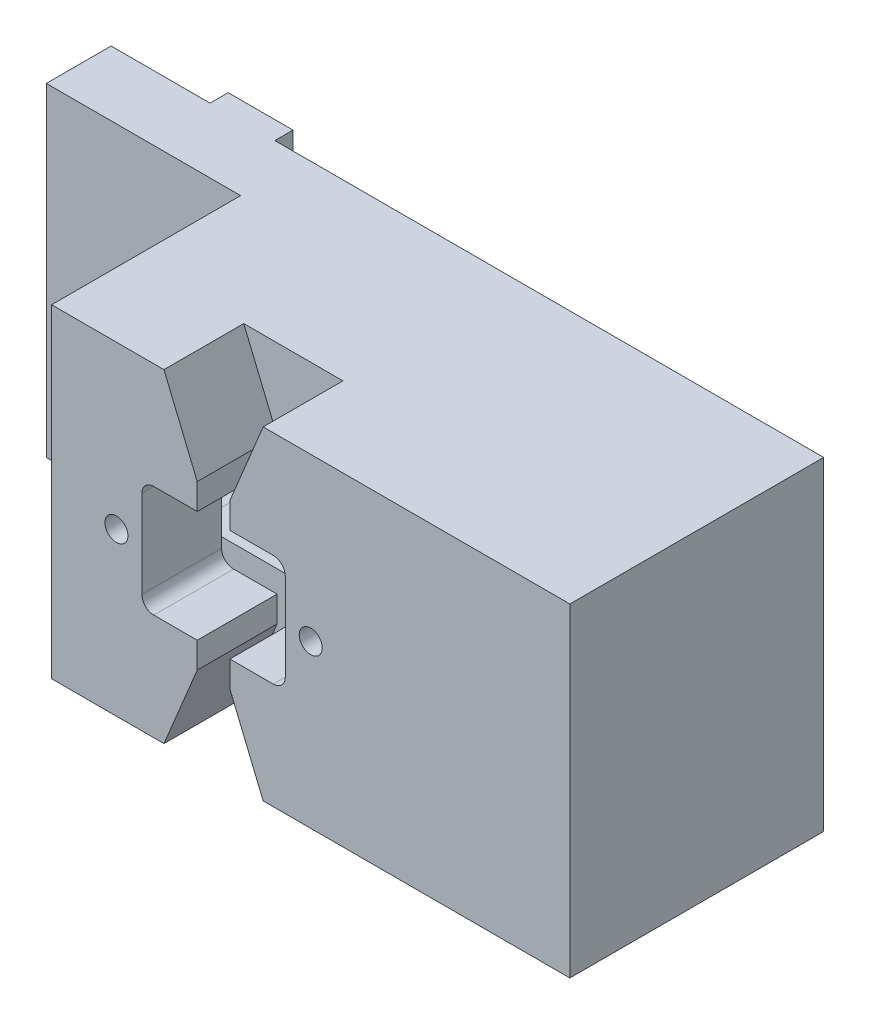
SolidWorks part; units mm, degrees
ref_plane "Front" through (0, 0, 0) normal (0, 0, 1) x (1, 0, 0)
ref_plane "Top" through (0, 0, 0) normal (0, 1, 0) x (1, 0, 0)
ref_plane "Right" through (0, 0, 0) normal (1, 0, 0) x (0, 0, -1)
sketch "Sketch1" plane through (0, 0, 0) normal (0, 0, 1) x (1, 0, 0)
  line L1 (0, 31.75) -> (69.85, 31.75)
  line L2 (0, 31.75) -> (0, 0)
  line L3 (0, 0) -> (69.85, 0)
  line L4 (69.85, 31.75) -> (69.85, 0)
  dimension "D1" = 69.85
  dimension "D2" = 31.75
extrude "Boss-Extrude1" add sketch "Sketch1" along normal blind 24.88
sketch "Sketch2" plane through (0, 0, 0) normal (0, 0, -1) x (-1, 0, 0)
  line L0 (-68.2625, 25.8953) -> (-50.8, 25.8953)
  line L2 (-50.8, 19.177) -> (-25.4, 19.177)
  line L3 (-25.4, 12.573) -> (-50.8, 12.573)
  line L4 (-50.8, 5.8547) -> (-68.2625, 5.8547)
  line L5 (-68.2625, 5.8547) -> (-68.2625, 25.8953)
  line L6 (-50.8, 19.177) -> (-50.8, 25.8953)
  line L7 (-50.8, 12.573) -> (-50.8, 5.8547)
  line L9 (-69.85, 0) -> (-69.85, 31.75) construction
  line L10 (0, 31.75) -> (0, 0) construction
  arc A5 (-25.4, 12.573) -> (-25.4, 19.177) centre (-25.4, 15.875) ccw
  point P12 (0, 15.875)
  dimension "D1" = 19.05
  dimension "D3" = 44.45
  dimension "D2" = 20.0406
  dimension "D4" = 1.5875
  dimension "D5" = 6.604
extrude "Cut-Extrude1" cut sketch "Sketch2" against normal blind 17.06
sketch "Sketch3" plane through (0, 0, 24.88) normal (0, 0, 1) x (1, 0, 0)
  line L0 (29.0688, 21.336) -> (40.7812, 21.336)
  line L1 (41.955, 20.1622) -> (41.955, 11.5878)
  line L2 (40.7812, 10.414) -> (29.0688, 10.414)
  line L3 (27.895, 11.5878) -> (27.895, 20.1622)
  line L4 (69.85, 31.75) -> (0, 31.75) construction
  arc A0 (40.7812, 21.336) -> (41.955, 20.1622) centre (40.7812, 20.1622) cw
  arc A1 (41.955, 11.5878) -> (40.7812, 10.414) centre (40.7812, 11.5878) cw
  arc A2 (29.0688, 10.414) -> (27.895, 11.5878) centre (29.0688, 11.5878) cw
  arc A3 (27.895, 20.1622) -> (29.0688, 21.336) centre (29.0688, 20.1622) cw
  arc A4 (25.4, 19.177) -> (25.4, 12.573) centre (25.4, 15.875) ccw construction
  point P14 (34.925, 10.414)
  dimension "D1" = 10.922
  dimension "D2" = 14.06
  dimension "D3" = 1.66
  dimension "D4" = 10.414
  dimension "D5" = 9.525
extrude "Cut-Extrude2" cut sketch "Sketch3" against normal up to surface (7.82 mm away) up to face at (48.4029, 15.875, 17.06)
sketch "Sketch4" plane through (0, 0, 24.88) normal (0, 0, 1) x (1, 0, 0)
  line L0 (30.0635, 31.75) -> (33.325, 23.876)
  line L1 (69.85, 31.75) -> (0, 31.75) construction
  line L2 (33.325, 23.876) -> (33.325, 21.336)
  line L3 (29.0688, 21.336) -> (40.7812, 21.336) construction
  line L4 (33.325, 21.336) -> (36.525, 21.336)
  line L5 (36.525, 21.336) -> (36.525, 23.876)
  line L6 (36.525, 23.876) -> (39.7865, 31.75)
  line L7 (39.7865, 31.75) -> (30.0635, 31.75)
  line L9 (34.925, 21.336) -> (34.925, 31.75) construction
  line L10 (33.325, 10.414) -> (33.325, 7.874)
  line L11 (29.0688, 10.414) -> (40.7812, 10.414) construction
  line L12 (33.325, 7.874) -> (30.0635, 0)
  line L13 (0, 0) -> (69.85, 0) construction
  line L14 (30.0635, 0) -> (39.7865, 0)
  line L15 (39.7865, 0) -> (36.525, 7.874)
  line L16 (36.525, 7.874) -> (36.525, 10.414)
  line L17 (40.7812, 10.414) -> (29.0688, 10.414) construction
  line L18 (36.525, 10.414) -> (33.325, 10.414)
  line L19 (34.925, 10.414) -> (34.925, 0) construction
  line L20 (40.7812, 21.336) -> (29.0688, 21.336) construction
  dimension "D1" = 45
  dimension "D2" = 2.54
  dimension "D3" = 3.2
extrude "Cut-Extrude3" cut sketch "Sketch4" against normal up to surface (7.82 mm away) up to face at (34.925, 11.4439, 17.06)
hole_wizard "#4-40 Tapped Hole1" positions "Sketch5" profile "Sketch6" tap size "#4-40" standard "ANSI Inch" end condition through all
sketch "Sketch5" plane through (0, 0, 17.06) normal (0, 0, -1) x (-1, 0, 0)
  line L0 (-34.925, 19.177) -> (-34.925, 12.573) construction
  line L1 (-27.895, 19.177) -> (-41.955, 19.177) construction
  line L2 (-41.955, 12.573) -> (-27.895, 12.573) construction
  line L5 (-25.4, 19.177) -> (-50.8, 19.177) construction
  point P0 (-44.45, 15.875)
  point P2 (-25.4, 15.875)
  dimension "D1" = 19.05
  dimension "D2" = 9.525
  dimension "D3" = 3.302
sketch "Sketch6" plane through (44.45, 15.875, 17.06) normal (1, 0, 0) x (0, 1, 0)
  line L0 (0, 0) -> (0, 7.82)
  line L1 (0, 7.82) -> (1.1303, 7.82)
  line L2 (1.1303, 7.82) -> (1.1303, 0)
  line L5 (1.1303, 0) -> (0, 0)
  line L11 (0, -6.35) -> (0, 107.95) construction
  dimension "Thru Tap Drill Dia." = 2.2606
  dimension "Thru Tap Drill Depth" = 7.82
cosmetic thread "Hole Thread1" parameters "D2"=2.8448
cosmetic thread "Hole Thread2" parameters "D2"=2.8448
sketch "Sketch7" plane through (0, 0, 0) normal (0, 0, -1) x (-1, 0, 0)
  line L0 (-69.85, 31.75) -> (0, 31.75) construction
  line L1 (-16.0515, 31.75) -> (-9.7015, 31.75)
  line L2 (-16.0515, 31.75) -> (-16.0515, 0)
  line L3 (-16.0515, 0) -> (-9.7015, 0)
  line L4 (-9.7015, 31.75) -> (-9.7015, 0)
  line L5 (0, 0) -> (-69.85, 0) construction
  dimension "D1" = 6.35
extrude "Boss-Extrude2" add sketch "Sketch7" along normal blind 1.778
sketch "Sketch8" plane through (0, 31.75, 0) normal (0, 1, 0) x (1, 0, 0)
  line L0 (9.7015, 0) -> (0, 0) construction
  line L1 (0, -24.88) -> (19.05, -24.88)
  line L2 (0, -24.88) -> (0, -6.35)
  line L3 (0, -6.35) -> (19.05, -6.35)
  line L4 (19.05, -24.88) -> (19.05, -6.35)
  dimension "D1" = 6.35
  dimension "D2" = 19.05
extrude "Cut-Extrude4" cut sketch "Sketch8" against normal through all
hole_wizard "1/4 Clearance Hole1" positions "Sketch10" profile "Sketch11" hole size "1/4" standard "ANSI Inch" end condition through all
sketch "Sketch10" plane through (0, 0, 6.35) normal (0, 0, 1) x (1, 0, 0)
  line L0 (0, 0) -> (9.7015, 0) construction
  line L1 (16.0515, 31.75) -> (16.0515, 0) construction
  point P0 (12.8765, 15.875)
  dimension "D1" = 15.875
  dimension "D2" = 3.175
sketch "Sketch11" plane through (12.8765, 15.875, 6.35) normal (1, 0, 0) x (0, -1, 0)
  line L0 (0, 0) -> (0, 8.128)
  line L1 (0, 8.128) -> (3.5712, 8.128)
  line L2 (3.5712, 8.128) -> (3.5712, 0)
  line L5 (3.5712, 0) -> (0, 0)
  line L11 (0, -6.35) -> (0, 107.95) construction
  dimension "Thru Hole Dia." = 7.1425
  dimension "Thru Hole Depth" = 8.128
